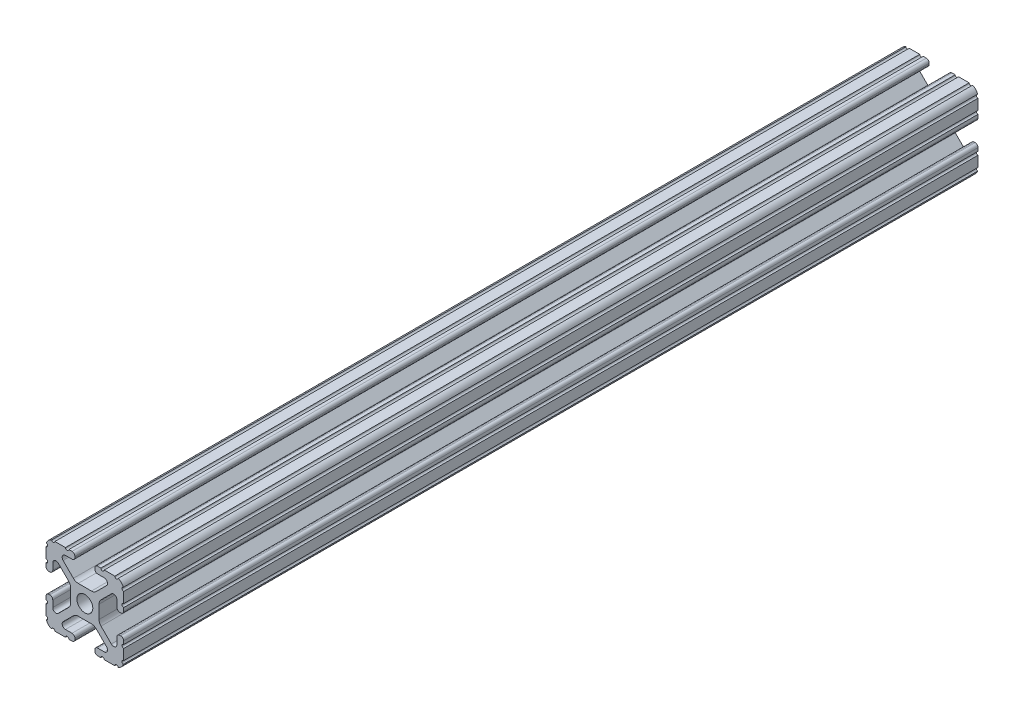
SolidWorks part; units mm, degrees
ref_plane "Front Plane" through (0, 0, 0) normal (0, 0, 1) x (1, 0, 0)
ref_plane "Top Plane" through (0, 0, 0) normal (0, 1, 0) x (1, 0, 0)
ref_plane "Right Plane" through (0, 0, 0) normal (1, 0, 0) x (0, 0, -1)
sketch "Sketch2" plane through (0, 0, 0) normal (0, 0, 1) x (1, 0, 0)
  line L0 (0, 12.7) -> (0, -12.7) construction
  line L1 (-12.7, 0) -> (12.7, 0) construction
  line L2 (3.2512, -12.7) -> (12.7, -12.7)
  line L3 (12.7, -12.7) -> (12.7, -3.2512)
  line L4 (3.2512, -12.7) -> (3.2512, -10.4902)
  line L5 (3.2512, -10.4902) -> (8.9276, -10.4902)
  line L6 (8.9276, -10.4902) -> (3.0856, -4.6482)
  line L7 (0, 0) -> (12.7, -12.7) construction
  line L8 (12.7, -3.2512) -> (10.4902, -3.2512)
  line L9 (10.4902, -3.2512) -> (10.4902, -8.9276)
  line L10 (10.4902, -8.9276) -> (4.6482, -3.0856)
  circle A0 centre (0, 0) radius 2.6035
  arc A1 (6.3485, -10.4902) -> (7.1039, -8.6665) centre (6.3485, -9.4219) ccw construction
  point P8 (0, -4.6482)
  dimension "Center Hole Diameter" = 5.207
  dimension "Rail Height" = 25.4
  dimension "Rail Width" = 25.4
  dimension "T-Slot Width" = 6.5024
  dimension "Slot Inner Width" = 14.8336
  dimension "Thickness" = 2.2098
  dimension "Slot Depth" = 5.842
  dimension "D1" = 2.2098
sketch "Sketch3" plane through (0, 0, 0) normal (1, 0, 0) x (0, 0, -1)
  line L0 (-139.7, -12.7) -> (139.7, -12.7) construction
  line L1 (-114.3, 0) -> (114.3, 0) construction
  dimension "Length" = 279.4
  dimension "D1" = 25.4
sketch "Sketch4" plane through (0, 0, 0) normal (0, 0, 1) x (1, 0, 0)
  line L0 (4.1904, -12.7) -> (10.1173, -12.7)
  line L1 (3.2512, -12.7) -> (12.7, -12.7) construction
  line L2 (3.2512, -12.7) -> (3.2512, -10.4902) construction
  line L3 (3.2512, -10.4902) -> (8.9276, -10.4902) construction
  line L4 (3.2512, -11.4294) -> (3.2512, -11.7608)
  line L5 (4.1904, -10.4902) -> (6.3485, -10.4902)
  line L6 (0, -4.6482) -> (2.164, -4.6482)
  line L7 (8.9276, -10.4902) -> (3.0856, -4.6482) construction
  line L8 (3.7373, -5.2999) -> (7.1039, -8.6665)
  line L9 (12.7, -12.7) -> (12.7, -3.2512) construction
  line L10 (10.4902, -8.9276) -> (4.6482, -3.0856) construction
  line L11 (10.4902, -3.2512) -> (10.4902, -8.9276) construction
  line L12 (10.4902, -6.3485) -> (10.4902, -4.1904)
  line L13 (12.7, -3.2512) -> (10.4902, -3.2512) construction
  line L14 (11.4294, -3.2512) -> (11.7608, -3.2512)
  line L15 (12.7, -4.1904) -> (12.7, -10.1173)
  line L16 (8.6665, -7.1039) -> (5.2999, -3.7373)
  line L17 (4.6482, 0) -> (4.6482, -2.164)
  line L18 (-12.7, 0) -> (12.7, 0) construction
  line L19 (0, -4.6482) -> (0, -2.6035)
  line L20 (0, 12.7) -> (0, -12.7) construction
  line L21 (4.6482, 0) -> (2.6035, 0)
  arc A0 (3.2512, -11.7608) -> (4.1904, -12.7) centre (4.1904, -11.7608) ccw
  arc A2 (3.2512, -11.4294) -> (4.1904, -10.4902) centre (4.1904, -11.4294) cw
  arc A3 (6.3485, -10.4902) -> (7.1039, -8.6665) centre (6.3485, -9.4219) ccw
  arc A4 (2.164, -4.6482) -> (3.7373, -5.2999) centre (2.164, -6.8732) cw
  arc A5 (10.1173, -12.7) -> (12.7, -10.1173) centre (10.1173, -10.1173) ccw
  arc A6 (8.6665, -7.1039) -> (10.4902, -6.3485) centre (9.4219, -6.3485) ccw
  arc A7 (10.4902, -4.1904) -> (11.4294, -3.2512) centre (11.4294, -4.1904) cw
  arc A8 (11.7608, -3.2512) -> (12.7, -4.1904) centre (11.7608, -4.1904) cw
  arc A9 (5.2999, -3.7373) -> (4.6482, -2.164) centre (6.8732, -2.164) cw
  circle A10 centre (0, 0) radius 2.6035 construction
  arc A11 (0, -2.6035) -> (2.6035, 0) centre (0, 0) ccw
  dimension "D1" = 2.5827
  dimension "D2" = 2.225
  dimension "D3" = 0.9392
extrude "Boss-Extrude1" add sketch "Sketch4" along normal mid plane 279.4
sketch "Sketch5" plane through (0, 0, 0) normal (0, 0, 1) x (1, 0, 0)
  line L0 (3.2512, -12.7) -> (12.7, -12.7) construction
  line L1 (4.1904, -10.4902) -> (6.3485, -10.4902) construction
  line L3 (0, 0) -> (12.7, -12.7) construction
  line L4 (6.3485, -10.4902) -> (6.3485, -12.7) construction
  line L5 (8.9276, -10.4902) -> (3.0856, -4.6482) construction
  circle A0 centre (10.3562, -12.7) radius 0.5524
  circle A1 centre (5.796, -12.7) radius 0.5524
  circle A2 centre (12.7, -10.3562) radius 0.5524
  circle A3 centre (12.7, -5.796) radius 0.5524
  point P10 (5.2694, -10.4902)
  point P12 (9.4219, -6.3485)
  dimension "D1" = 1.1049
extrude "Cut-Extrude1" cut sketch "Sketch5" against normal through all both and the other way through all
mirror "Mirror1" about plane through (0, 0, 0) normal (1, 0, 0) of bodies 137 134
mirror "Mirror2" about plane through (0, 0, 0) normal (0, 1, 0) of bodies 135
equation "\"D1@Boss-Extrude1\"=\"Length@Sketch3\""
equation "\"D1@Sketch2\"=\"Thickness@Sketch2\""
equation "\"D2@Sketch4\"=\"Slot Inner Width@Sketch2\"*0.15"
equation "\"D1@Sketch4\"=\"D3@Sketch4\"*2.75"
equation "\"D3@Sketch4\"=\"Thickness@Sketch2\"*0.425"
equation "\"D1@Sketch5\"=\"Thickness@Sketch2\"*0.5"
